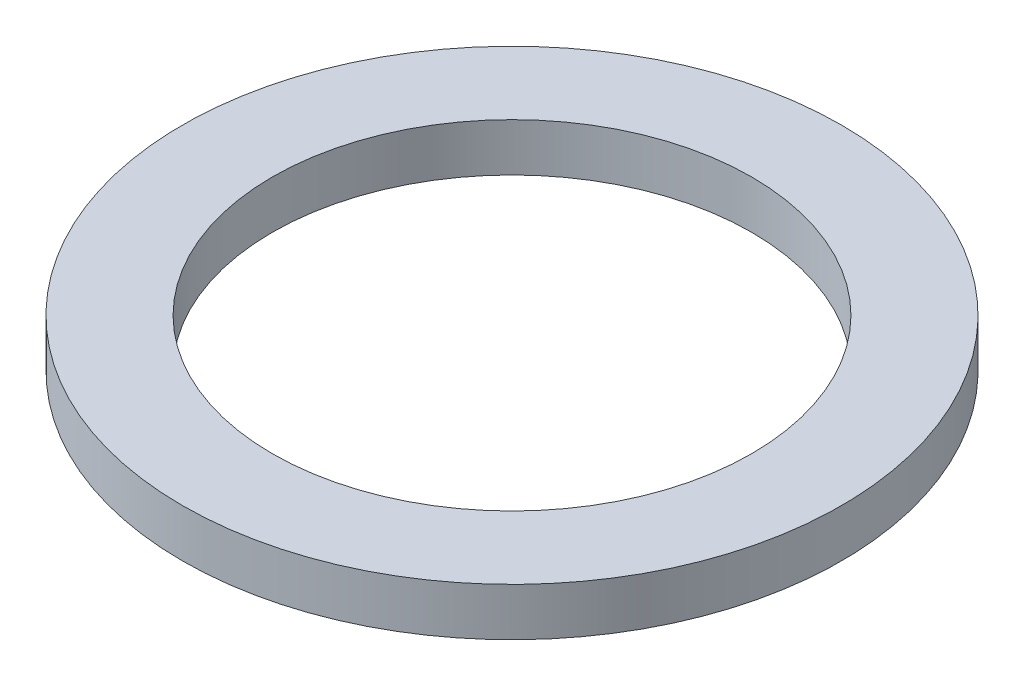
SolidWorks part; units mm, degrees
ref_plane "Alzado" through (0, 0, 0) normal (0, 0, 1) x (1, 0, 0)
ref_plane "Planta" through (0, 0, 0) normal (0, 1, 0) x (1, 0, 0)
ref_plane "Vista lateral" through (0, 0, 0) normal (1, 0, 0) x (0, 0, -1)
sketch "Croquis1" plane through (0, 0, 0) normal (0, 1, 0) x (1, 0, 0)
  circle A0 centre (0, 0) radius 10
  circle A1 centre (0, 0) radius 13.75
  dimension "D1" = 20
  dimension "D2" = 27.5
extrude "Saliente-Extruir1" add sketch "Croquis1" along normal blind 2
